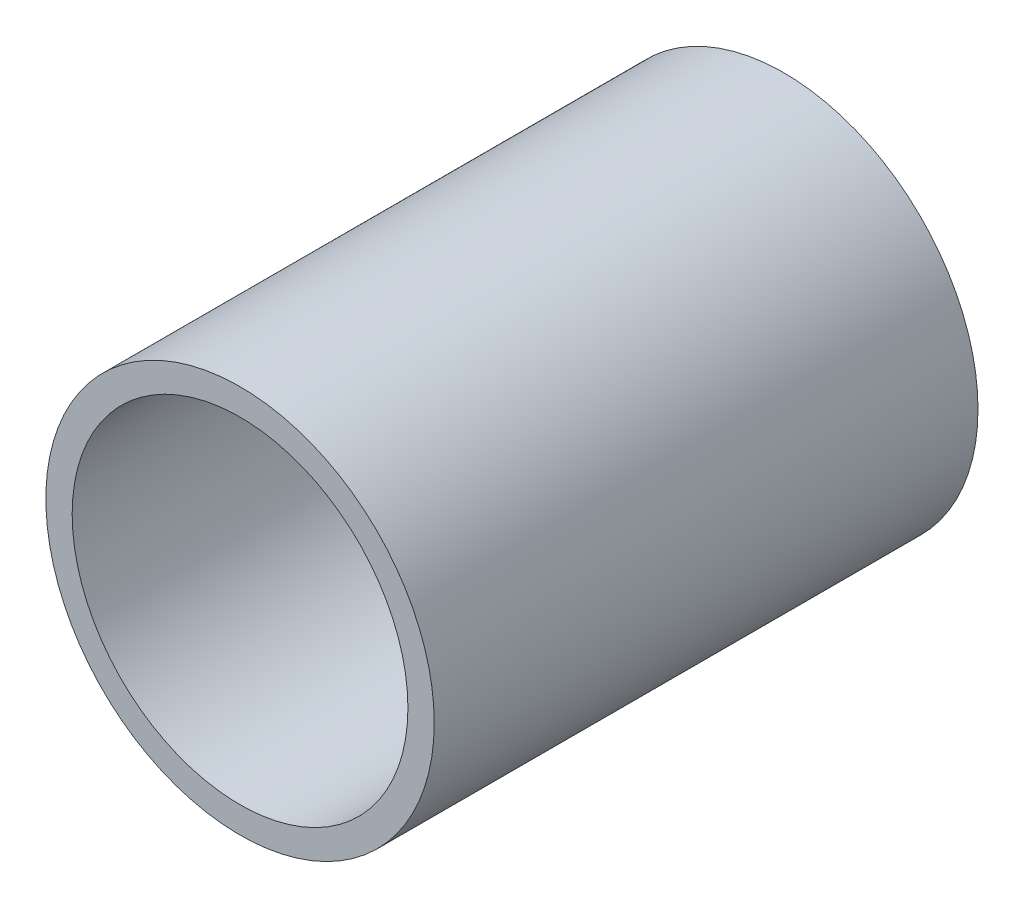
SolidWorks part; units mm, degrees
ref_plane "Front Plane" through (0, 0, 0) normal (0, 0, 1) x (1, 0, 0)
ref_plane "Top Plane" through (0, 0, 0) normal (0, 1, 0) x (1, 0, 0)
ref_plane "Right Plane" through (0, 0, 0) normal (1, 0, 0) x (0, 0, -1)
sketch "Sketch1" plane through (0, 0, 0) normal (0, 0, 1) x (1, 0, 0)
  circle A0 centre (0, 0) radius 25
  dimension "D1" = 50
extrude "Boss-Extrude1" add sketch "Sketch1" along normal blind 70
sketch "Sketch2" plane through (0, 0, 70) normal (0, 0, 1) x (1, 0, 0)
  circle A0 centre (0, 0) radius 21.6118
  circle A1 centre (0, 0) radius 25 construction
  dimension "D1" = 3.3882
extrude "Cut-Extrude1" cut sketch "Sketch2" against normal blind 60
